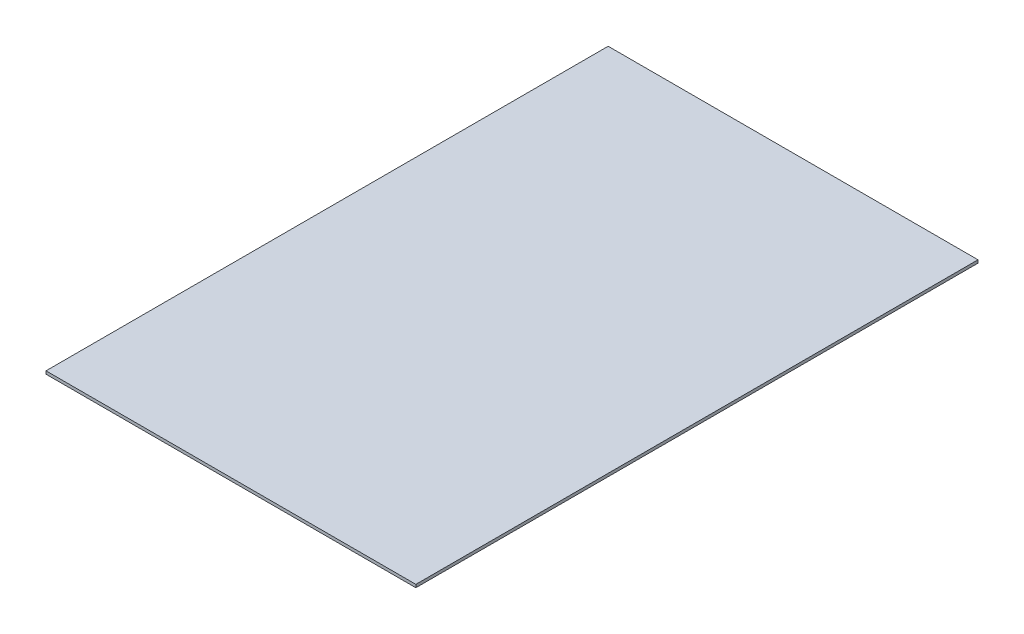
SolidWorks part; units mm, degrees
ref_plane "Front Plane" through (0, 0, 0) normal (0, 0, 1) x (1, 0, 0)
ref_plane "Top Plane" through (0, 0, 0) normal (0, 1, 0) x (1, 0, 0)
ref_plane "Right Plane" through (0, 0, 0) normal (1, 0, 0) x (0, 0, -1)
sketch "Sketch1" plane through (0, 0, 0) normal (0, 1, 0) x (1, 0, 0)
  line L1 (-158.75, -241.3) -> (158.75, -241.3)
  line L2 (-158.75, -241.3) -> (-158.75, 241.3)
  line L3 (-158.75, 241.3) -> (158.75, 241.3)
  line L4 (158.75, -241.3) -> (158.75, 241.3)
  line L5 (-158.75, -241.3) -> (158.75, 241.3) construction
  line L6 (-158.75, 241.3) -> (158.75, -241.3) construction
  point P0 (0, 0)
  dimension "D1" = 317.5
  dimension "D2" = 482.6
extrude "Boss-Extrude1" add sketch "Sketch1" along normal blind 2.54
